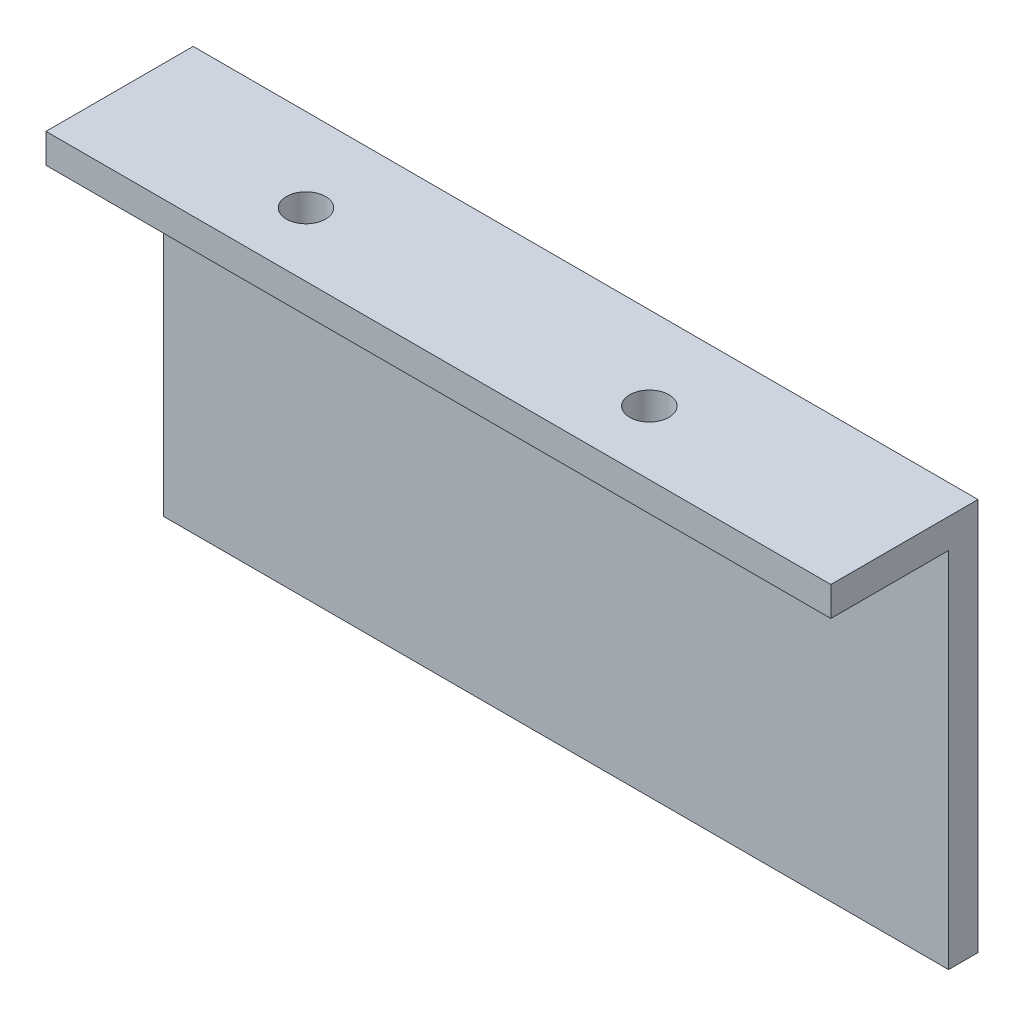
SolidWorks part; units mm, degrees
ref_plane "Front Plane" through (0, 0, 0) normal (0, 0, 1) x (1, 0, 0)
ref_plane "Top Plane" through (0, 0, 0) normal (0, 1, 0) x (1, 0, 0)
ref_plane "Right Plane" through (0, 0, 0) normal (1, 0, 0) x (0, 0, -1)
sketch "Sketch1" plane through (0, 0, 0) normal (0, 0, 1) x (1, 0, 0)
  line L1 (-40, 20) -> (40, 20)
  line L2 (-40, 20) -> (-40, -20)
  line L3 (-40, -20) -> (40, -20)
  line L4 (40, 20) -> (40, -20)
  line L5 (-40, 20) -> (40, -20) construction
  line L6 (-40, -20) -> (40, 20) construction
  point P0 (0, 0)
  dimension "D1" = 40
  dimension "D2" = 80
extrude "Boss-Extrude1" add sketch "Sketch1" along normal blind 3
sketch "Sketch2" plane through (0, 0, 3) normal (0, 0, 1) x (1, 0, 0)
  line L0 (40, -20) -> (40, 20) construction
  line L1 (-40, 20) -> (40, 20)
  line L2 (-40, 20) -> (-40, 17)
  line L3 (-40, 17) -> (40, 17)
  line L4 (40, 20) -> (40, 17)
  dimension "D1" = 3
extrude "Boss-Extrude2" add sketch "Sketch2" along normal blind 12
sketch "Sketch3" plane through (0, 20, 0) normal (0, 1, 0) x (1, 0, 0)
  line L0 (40, 0) -> (-40, 0) construction
  line L2 (-40, -15) -> (-40, 0) construction
  circle A0 centre (15, -8.5) radius 2
  circle A1 centre (-20, -8.5) radius 2
  dimension "D1" = 4
  dimension "D2" = 4
  dimension "D3" = 8.5
  dimension "D4" = 8.5
  dimension "D5" = 20
  dimension "D6" = 35
extrude "Cut-Extrude1" cut sketch "Sketch3" against normal blind 12
